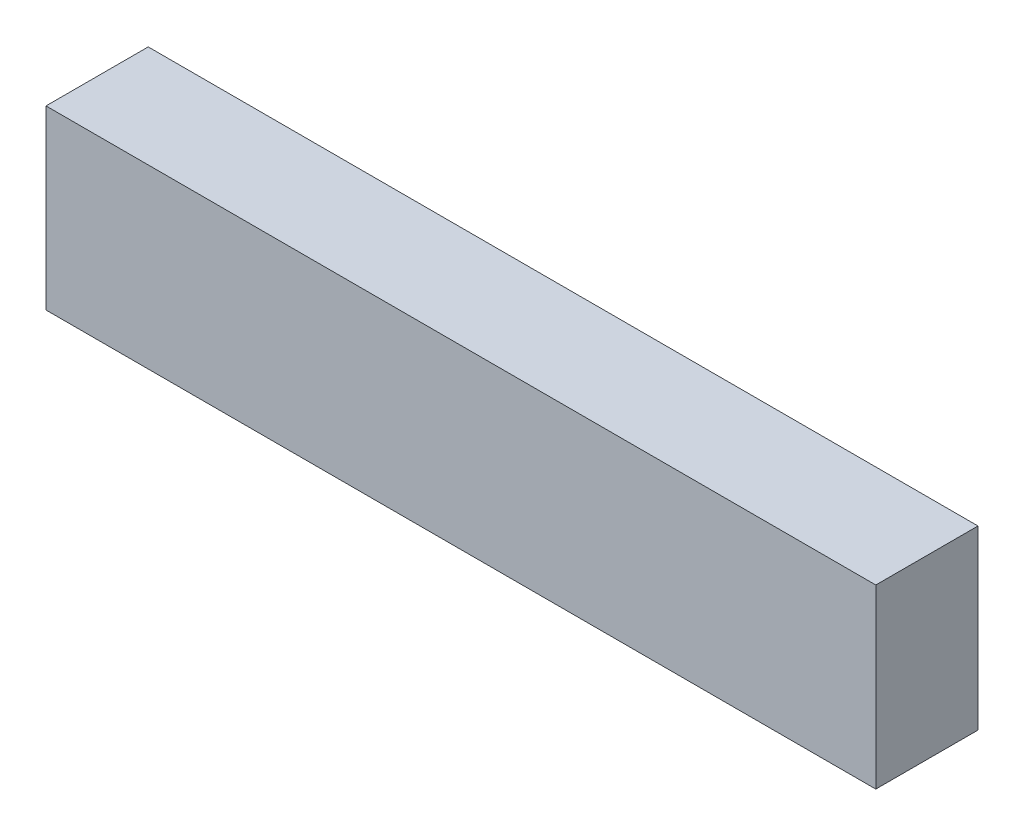
SolidWorks part; units mm, degrees
ref_plane "Front Plane" through (0, 0, 0) normal (0, 0, 1) x (1, 0, 0)
ref_plane "Top Plane" through (0, 0, 0) normal (0, 1, 0) x (1, 0, 0)
ref_plane "Right Plane" through (0, 0, 0) normal (1, 0, 0) x (0, 0, -1)
sketch "Sketch1" plane through (0, 0, 0) normal (0, 0, 1) x (1, 0, 0)
  line L0 (-79.2368, 30.39) -> (-19.9755, 30.39) construction
  line L1 (-79.0368, 30.19) -> (-20.1755, 30.19)
  line L2 (-79.0368, 30.19) -> (-79.0368, 17.65)
  line L3 (-79.0368, 17.65) -> (-20.1755, 17.65)
  line L4 (-20.1755, 30.19) -> (-20.1755, 17.65)
  line L5 (-19.9755, 30.39) -> (-19.9755, 17.45) construction
  line L6 (-19.9755, 17.45) -> (-79.2368, 17.45) construction
  line L7 (-79.2368, 30.39) -> (-79.2368, 17.45) construction
  dimension "D1" = 0.2
  dimension "D2" = 0.2
  dimension "D3" = 0.2
  dimension "D4" = 0.2
extrude "Boss-Extrude1" add sketch "Sketch1" along normal blind 7.25 contours L1 L4 L3 L2
shell "Shell1" thickness 0.5
equation "\"D2@Sketch1\"=\"D1@Sketch1\""
equation "\"D3@Sketch1\"=\"D1@Sketch1\""
equation "\"D4@Sketch1\"=\"D1@Sketch1\""
